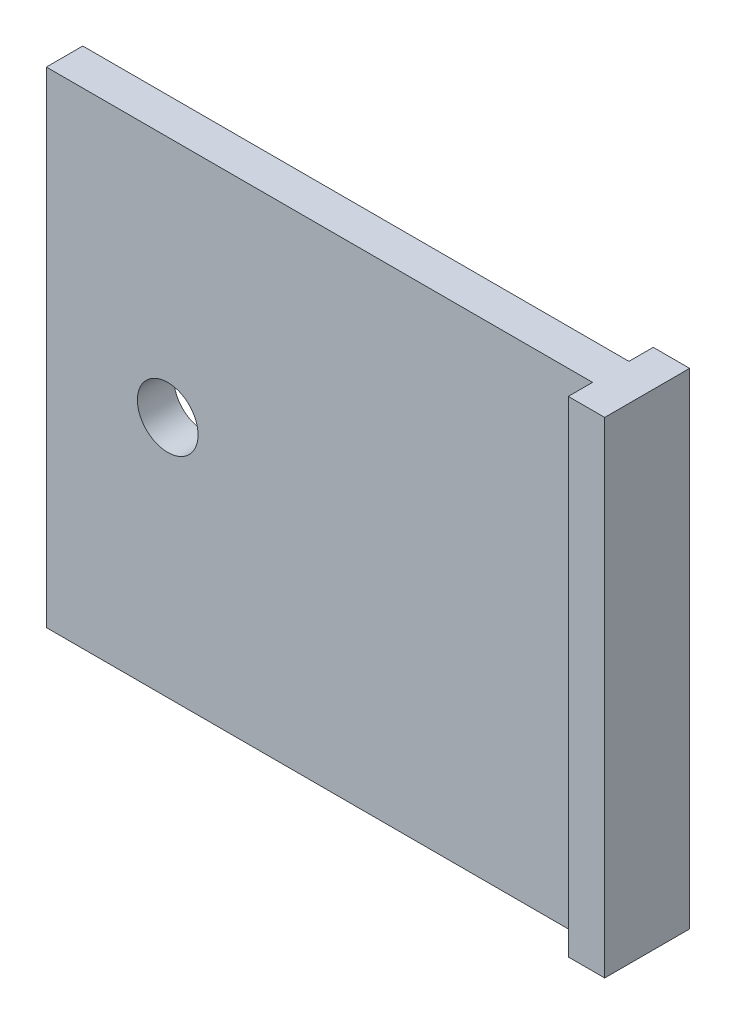
SolidWorks part; units mm, degrees
ref_plane "前基準面" through (0, 0, 0) normal (0, 0, 1) x (1, 0, 0)
ref_plane "上基準面" through (0, 0, 0) normal (0, 1, 0) x (1, 0, 0)
ref_plane "右基準面" through (0, 0, 0) normal (1, 0, 0) x (0, 0, -1)
sketch "草圖1" plane through (0, 0, 0) normal (0, 0, 1) x (1, 0, 0)
  line L0 (22.5, 0) -> (-12.5, 0) construction
  line L1 (-22.5, -20) -> (22.5, -20)
  line L2 (-22.5, -20) -> (-22.5, 20)
  line L3 (-22.5, 20) -> (22.5, 20)
  line L4 (22.5, -20) -> (22.5, 20)
  line L5 (-22.5, -20) -> (22.5, 20) construction
  line L6 (-22.5, 20) -> (22.5, -20) construction
  circle A1 centre (-12.5, 0) radius 2.5
  point P0 (0, 0)
  dimension "D3" = 35
  dimension "D4" = 5
  dimension "D1" = 45
  dimension "D2" = 40
extrude "填料-伸長1" add sketch "草圖1" along normal blind 3
sketch "草圖2" plane through (0, 0, 0) normal (1, 0, 0) x (0, 0, -1)
  line L10 (-5, 20) -> (2, 20)
  line L12 (-5, -20) -> (2, -20)
  line L19 (2, -20) -> (2, 20)
  line L20 (-5, 20) -> (-5, -20)
  dimension "D1" = 40
  dimension "D2" = 7
extrude "填料-伸長2" add sketch "草圖2" along normal blind 3 from surface at 22.5 starting at face at (22.5, 0, 1.5)
